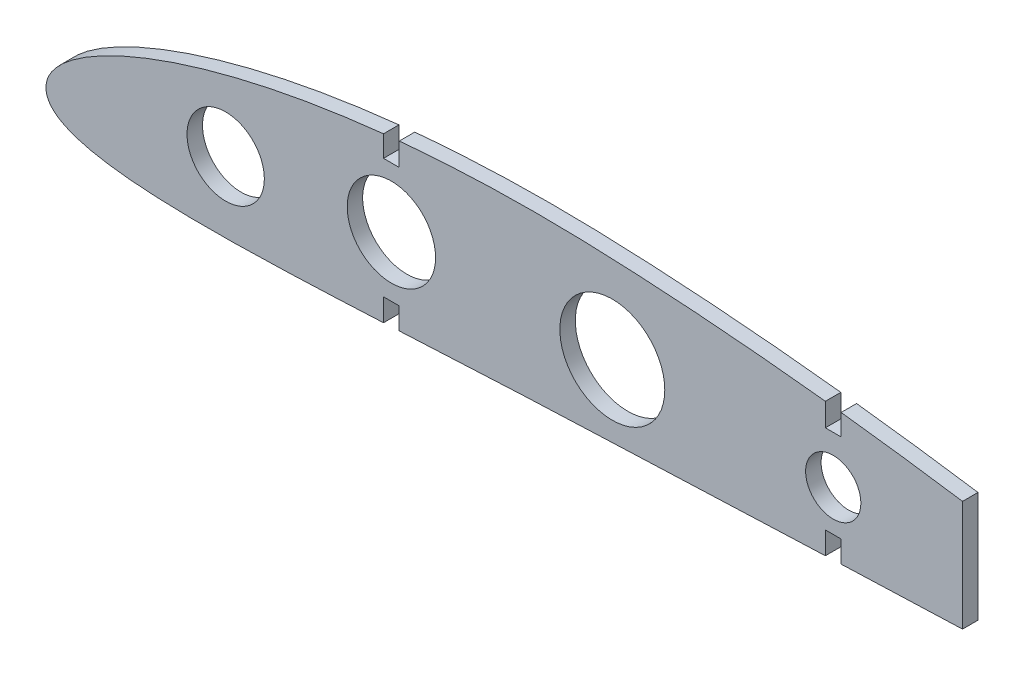
SolidWorks part; units mm, degrees
material "Фанера"
ref_plane "Front Plane" through (0, 0, 0) normal (0, 0, 1) x (1, 0, 0)
ref_plane "Top Plane" through (0, 0, 0) normal (0, 1, 0) x (1, 0, 0)
ref_plane "Right Plane" through (0, 0, 0) normal (1, 0, 0) x (0, 0, -1)
curve "Кривая5"
  spline degree 3 poles (0.048, 0.6214, 0) (0.0227, 0.3735, 0) (-0.0278, -0.1225, 0) (0.078, -0.8844, 0) (0.3497, -1.6388, 0) (0.8143, -2.3651, 0) (1.4635, -3.0393, 0) (2.291, -3.661, 0) (3.3059, -4.2358, 0) (4.5353, -4.7737, 0) (6.0297, -5.2822, 0) (7.869, -5.7653, 0) (10.1688, -6.2217, 0) (13.0754, -6.6396, 0) (16.7281, -6.993, 0) (21.19, -7.2473, 0) (26.4, -7.3766, 0) (32.1974, -7.3763, 0) (38.3978, -7.2614, 0) (44.8576, -7.0566, 0) (51.4865, -6.7865, 0) (58.231, -6.4723, 0) (65.0521, -6.1329, 0) (71.9108, -5.784, 0) (78.7714, -5.4397, 0) (85.6105, -5.111, 0) (92.4321, -4.805, 0) (99.255, -4.532, 0) (106.0974, -4.2783, 0) (112.9692, -4.0031, 0) (119.8644, -3.7232, 0) (126.7739, -3.4401, 0) (133.6816, -3.1587, 0) (140.5819, -2.8824, 0) (147.472, -2.6139, 0) (154.3526, -2.3556, 0) (161.225, -2.1094, 0) (168.0909, -1.8766, 0) (174.9516, -1.6586, 0) (181.8086, -1.4564, 0) (188.6632, -1.2704, 0) (195.5166, -1.1011, 0) (202.3695, -0.9486, 0) (209.2212, -0.8129, 0) (216.0668, -0.6936, 0) (222.8864, -0.5903, 0) (229.6176, -0.5029, 0) (236.0874, -0.4315, 0) (241.9808, -0.3765, 0) (246.559, -0.3395, 0) (249.1205, -0.3213, 0) (250, -0.315, 0) knots 0 0 0 0 0.002941 0.005884 0.009016 0.012365 0.016008 0.020037 0.024574 0.029784 0.035897 0.04324 0.052276 0.063635 0.077983 0.095698 0.11652 0.139661 0.164312 0.189919 0.216157 0.242838 0.269834 0.296993 0.324123 0.351139 0.378036 0.404946 0.431961 0.459078 0.486347 0.513641 0.540929 0.568176 0.59538 0.622543 0.649673 0.676775 0.703855 0.730919 0.757971 0.785018 0.812062 0.839103 0.866132 0.893099 0.919831 0.94581 0.969681 0.98959 1 1 1 1
curve "Кривая6"
  spline degree 3 poles (250, 0.315, 0) (249.1557, 0.545, 0) (246.7202, 1.2085, 0) (242.3913, 2.3583, 0) (236.8498, 3.7876, 0) (230.7799, 5.298, 0) (224.4559, 6.8129, 0) (218.0305, 8.2916, 0) (211.5624, 9.7197, 0) (205.0724, 11.0924, 0) (198.568, 12.4079, 0) (192.0524, 13.6653, 0) (185.5276, 14.8641, 0) (178.9953, 16.0034, 0) (172.4571, 17.0824, 0) (165.9143, 18.0998, 0) (159.3687, 19.0545, 0) (152.8218, 19.9449, 0) (146.2754, 20.7693, 0) (139.7314, 21.5257, 0) (133.1918, 22.212, 0) (126.6587, 22.8257, 0) (120.1368, 23.364, 0) (113.6286, 23.8247, 0) (107.1527, 24.2002, 0) (100.7411, 24.4984, 0) (94.4118, 24.6866, 0) (88.1559, 24.7401, 0) (81.949, 24.6588, 0) (75.7805, 24.441, 0) (69.6537, 24.0819, 0) (63.5754, 23.578, 0) (57.5552, 22.9249, 0) (51.6058, 22.1191, 0) (45.7444, 21.1566, 0) (39.9959, 20.0354, 0) (34.3979, 18.7563, 0) (29.0104, 17.3276, 0) (23.9258, 15.7719, 0) (19.2707, 14.1343, 0) (15.1791, 12.4833, 0) (11.7405, 10.8956, 0) (8.9594, 9.4296, 0) (6.7609, 8.1086, 0) (5.0337, 6.9246, 0) (3.6717, 5.8542, 0) (2.5921, 4.8713, 0) (1.7382, 3.9526, 0) (1.0699, 3.0809, 0) (0.5716, 2.2416, 0) (0.2158, 1.4308, 0) (0.1023, 0.8832, 0) (0.048, 0.6214, 0) knots 0 0 0 0 0.010162 0.029313 0.052012 0.076619 0.101948 0.127526 0.153184 0.178868 0.204558 0.230246 0.255926 0.281594 0.307246 0.332878 0.358485 0.384061 0.409603 0.435104 0.460559 0.485959 0.511303 0.536552 0.561723 0.586629 0.611085 0.635251 0.659272 0.683164 0.706922 0.730536 0.753983 0.777235 0.800246 0.822951 0.845237 0.866916 0.887662 0.906968 0.924203 0.938879 0.950932 0.960693 0.968647 0.975233 0.980795 0.985584 0.989782 0.993521 0.996902 1 1 1 1
sketch "Эскиз1" plane through (0, 0, 0) normal (0, 0, 1) x (1, 0, 0)
  line L0 (250.1305, 0) -> (250.1305, 54.8427) construction
  line L1 (0, 0) -> (0, 70.5199) construction
  line L2 (0, 0) -> (253.0634, 0) construction
  line L3 (62.5326, 62.6361) -> (62.5326, -41.5636) construction
  line L4 (142.5326, 67.9319) -> (142.5326, 25.1988) construction
  line L5 (175.0913, 63.8571) -> (175.0913, -32.3947) construction
  line L6 (32.5326, -14.3434) -> (32.5326, 29.5903) construction
  line L7 (142.5326, 21.1988) -> (142.5326, -57.0034) construction
  line L8 (61.1076, 19.4501) -> (63.9576, 19.4501)
  line L9 (61.1076, 19.4501) -> (61.1076, 23.3031)
  line L11 (63.9576, 19.4501) -> (63.9576, 23.5885)
  line L12 (61.1076, 19.4501) -> (62.5326, 23.4501) construction
  line L13 (62.5326, 23.4501) -> (63.9576, 19.4501) construction
  line L15 (61.1076, -6.3284) -> (61.1076, -2.2577)
  line L16 (61.1076, -2.2577) -> (63.9576, -2.2577)
  line L17 (63.9576, -6.1866) -> (63.9576, -2.2577)
  line L18 (62.5326, -6.2577) -> (63.9576, -2.2577) construction
  line L19 (61.1076, -2.2577) -> (62.5326, -6.2577) construction
  line L20 (141.1076, 17.1988) -> (143.9576, 17.1988)
  line L21 (141.1076, 17.1988) -> (141.1076, 21.3608)
  line L23 (143.9576, 17.1988) -> (143.9576, 21.0336)
  line L24 (141.1076, 17.1988) -> (142.5326, 21.1988) construction
  line L25 (142.5326, 21.1988) -> (143.9576, 17.1988) construction
  line L26 (165.9405, 18.0854) -> (165.9405, -1.9504)
  line L28 (141.1076, -2.8629) -> (141.1076, 1.1931)
  line L29 (141.1076, 1.1931) -> (143.9576, 1.1931)
  line L30 (143.9576, -2.7512) -> (143.9576, 1.1931)
  line L31 (142.5326, -2.8069) -> (143.9576, 1.1931) construction
  line L32 (141.1076, 1.1931) -> (142.5326, -2.8069) construction
  arc A0 (250, 0.315) -> (250, -0.315) centre (249.685, 0) cw
  circle A1 centre (62.5326, 8.5962) radius 8
  circle A2 centre (142.5326, 8.5962) radius 5
  circle A3 centre (32.5326, 5.4481) radius 7
  circle A5 centre (102.5326, 8.5962) radius 9.5
  arc A6 (175.0913, 16.6448) -> (175.0913, -1.657) centre (175.0913, 7.4939) ccw
  spline S2 degree 3 poles (0.048, 0.6214) (0.0227, 0.3735) (-0.0278, -0.1225) (0.078, -0.8844) (0.3497, -1.6388) (0.8143, -2.3651) (1.4635, -3.0393) (2.291, -3.661) (3.3059, -4.2358) (4.5353, -4.7737) (6.0297, -5.2822) (7.869, -5.7653) (10.1688, -6.2217) (13.0754, -6.6396) (16.7281, -6.993) (21.19, -7.2473) (26.4, -7.3766) (32.1974, -7.3763) (38.3978, -7.2614) (44.8576, -7.0566) (51.4865, -6.7865) (56.9206, -6.5334) (60.1398, -6.3761) (61.1076, -6.3284) knots 0 0 0 0 0.002941 0.005884 0.009016 0.012365 0.016008 0.020037 0.024574 0.029784 0.035897 0.04324 0.052276 0.063635 0.077983 0.095698 0.11652 0.139661 0.164312 0.189919 0.216157 0.242838 0.254307 0.254307 0.254307 0.254307
  spline S3 degree 3 poles (250, 0.315) (249.1557, 0.545) (246.7202, 1.2085) (242.3913, 2.3583) (236.8498, 3.7876) (230.7799, 5.298) (224.4559, 6.8129) (218.0305, 8.2916) (211.5624, 9.7197) (205.0724, 11.0924) (198.568, 12.4079) (192.0524, 13.6653) (185.5276, 14.8641) (178.9953, 16.0034) (172.4571, 17.0824) (165.9143, 18.0998) (159.3687, 19.0545) (152.8218, 19.9449) (147.6839, 20.5919) (144.7288, 20.9433) (143.9576, 21.0336) knots 0 0 0 0 0.010162 0.029313 0.052012 0.076619 0.101948 0.127526 0.153184 0.178868 0.204558 0.230246 0.255926 0.281594 0.307246 0.332878 0.358485 0.384061 0.409603 0.418619 0.418619 0.418619 0.418619
  spline S4 degree 3 poles (61.1076, 23.3031) (59.9179, 23.1768) (56.7397, 22.8145) (51.6058, 22.1191) (45.7444, 21.1566) (39.9959, 20.0354) (34.3979, 18.7563) (29.0104, 17.3276) (23.9258, 15.7719) (19.2707, 14.1343) (15.1791, 12.4833) (11.7405, 10.8956) (8.9594, 9.4296) (6.7609, 8.1086) (5.0337, 6.9246) (3.6717, 5.8542) (2.5921, 4.8713) (1.7382, 3.9526) (1.0699, 3.0809) (0.5716, 2.2416) (0.2158, 1.4308) (0.1023, 0.8832) (0.048, 0.6214) knots 0.740091 0.740091 0.740091 0.740091 0.753983 0.777235 0.800246 0.822951 0.845237 0.866916 0.887662 0.906968 0.924203 0.938879 0.950932 0.960693 0.968647 0.975233 0.980795 0.985584 0.989782 0.993521 0.996902 1 1 1 1
  spline S5 degree 3 poles (63.9576, -6.1866) (64.3178, -6.1685) (66.9697, -6.0353) (71.9108, -5.784) (78.7714, -5.4397) (85.6105, -5.111) (92.4321, -4.805) (99.255, -4.532) (106.0974, -4.2783) (112.9692, -4.0031) (119.8644, -3.7232) (126.7739, -3.4401) (133.8556, -3.1516) (138.6334, -2.9604) (141.1076, -2.8629) knots 0.265565 0.265565 0.265565 0.265565 0.269834 0.296993 0.324123 0.351139 0.378036 0.404946 0.431961 0.459078 0.486347 0.513641 0.540929 0.570237 0.570237 0.570237 0.570237
  spline S6 degree 3 poles (143.9576, -2.7512) (145.1302, -2.7056) (148.5961, -2.5717) (154.3526, -2.3556) (161.225, -2.1094) (168.0909, -1.8766) (174.9516, -1.6586) (181.8086, -1.4564) (188.6632, -1.2704) (195.5166, -1.1011) (202.3695, -0.9486) (211.4992, -0.7677) (220.6031, -0.6199) (229.6176, -0.5029) (236.0874, -0.4315) (241.9808, -0.3765) (246.559, -0.3395) (249.1205, -0.3213) (250, -0.315) knots 0.58149 0.58149 0.58149 0.58149 0.59538 0.622543 0.649673 0.676775 0.703855 0.730919 0.757971 0.785018 0.812062 0.839103 0.893099 0.919831 0.94581 0.969681 0.98959 1 1 1 1
  spline S7 degree 3 poles (141.1076, 21.3608) (140.6472, 21.4126) (138.0081, 21.7065) (133.1918, 22.212) (126.6587, 22.8257) (120.1368, 23.364) (113.6286, 23.8247) (107.1527, 24.2002) (100.7411, 24.4984) (94.4118, 24.6866) (88.1559, 24.7401) (81.949, 24.6588) (75.7805, 24.441) (69.7854, 24.0896) (65.8508, 23.7665) (63.9576, 23.5885) knots 0.429724 0.429724 0.429724 0.429724 0.435104 0.460559 0.485959 0.511303 0.536552 0.561723 0.586629 0.611085 0.635251 0.659272 0.683164 0.706922 0.729004 0.729004 0.729004 0.729004
  point P22 (62.5326, 23.4501)
  point P23 (62.5326, -6.2577)
  point P26 (32.5326, 18.2506)
  point P27 (32.5326, -7.3543)
  point P30 (62.5326, 23.4501)
  point P31 (62.5326, -6.2577)
  point P40 (142.5326, 21.1988)
  point P43 (142.5326, -2.8069)
  point P53 (175.0913, 16.6448)
  point P56 (175.0913, -1.657)
  dimension "D3" = 16
  dimension "D8" = 14
  dimension "D10" = 10
  dimension "D9" = 19
  dimension "D27" = 9.1509
  dimension "D1" = 250.1305
  dimension "D2" = 62.5326
  dimension "D4" = 80
  dimension "D5" = 75.0391
  dimension "D6" = 29.7079
  dimension "D7" = 14.8539
  dimension "D11" = 40
  dimension "D12" = 30
  dimension "D13" = 25.6049
  dimension "D14" = 12.8025
  dimension "D15" = 2.85
  dimension "D16" = 4
  dimension "D17" = 1.425
  dimension "D18" = 2.85
  dimension "D19" = 4
  dimension "D20" = 1.425
  dimension "D21" = 2.85
  dimension "D22" = 4
  dimension "D23" = 1.425
  dimension "D24" = 2.85
  dimension "D25" = 4
  dimension "D26" = 1.425
extrude "Бобышка-Вытянуть1" add sketch "Эскиз1" along normal mid plane 2.8 contours L21 S7 L11 L8 L9 S4 S2 L15 L16 L17 S5 L28 L29 L30 S6 L26 S3 L23 L20 A1 A2 A3 A5
equation "\"D2@Эскиз1\"=\"D1@Эскиз1\"/4"
equation "\"D7@Эскиз1\"=\"D6@Эскиз1\"/2"
equation "\"D5@Эскиз1\"=\"D1@Эскиз1\"*0.3"
equation "\"D14@Эскиз1\"=\"D13@Эскиз1\"/2"
equation "\"t\"= 2.85"
equation "\"D17@Эскиз1\"=\"D15@Эскиз1\"/2"
equation "\"D18@Эскиз1\"=\"t\""
equation "\"D20@Эскиз1\"=\"D18@Эскиз1\"/2"
equation "\"D21@Эскиз1\"=\"t\""
equation "\"D23@Эскиз1\"=\"D21@Эскиз1\"/2"
equation "\"D24@Эскиз1\"=\"t\""
equation "\"D26@Эскиз1\"=\"D24@Эскиз1\"/2"
